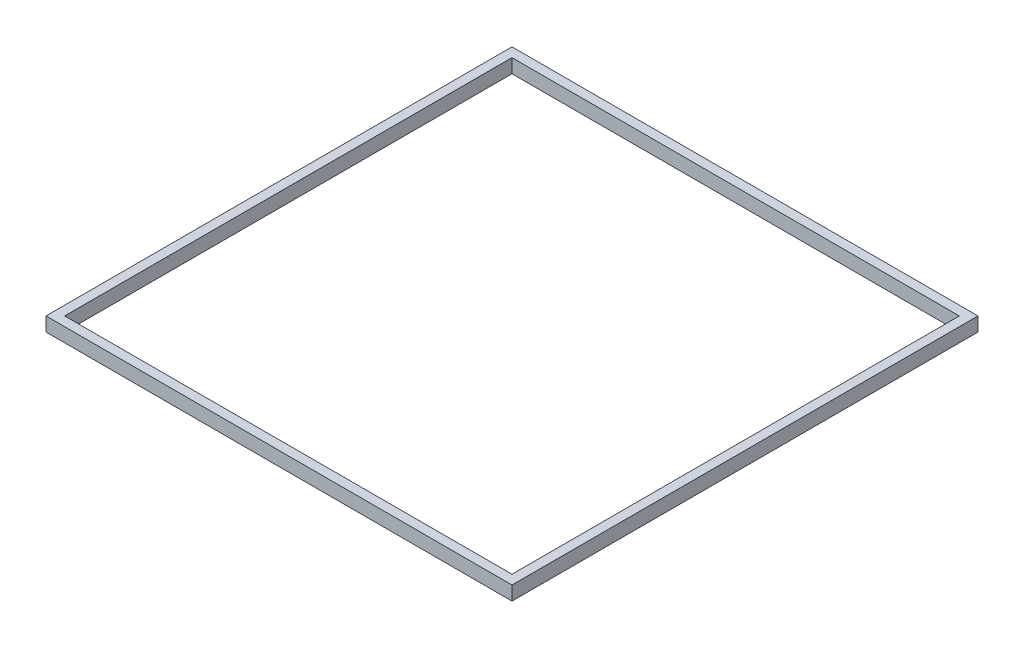
SolidWorks part; units mm, degrees
ref_plane "Front Plane" through (0, 0, 0) normal (0, 0, 1) x (1, 0, 0)
ref_plane "Top Plane" through (0, 0, 0) normal (0, 1, 0) x (1, 0, 0)
ref_plane "Right Plane" through (0, 0, 0) normal (1, 0, 0) x (0, 0, -1)
sketch "Sketch1" plane through (0, 0, 0) normal (0, 1, 0) x (1, 0, 0)
  line L0 (125, -125) -> (125, 125)
  line L1 (120, -120) -> (-120, -120)
  line L2 (120, -120) -> (120, 120)
  line L3 (120, 120) -> (-120, 120)
  line L4 (-120, -120) -> (-120, 120)
  line L5 (120, -120) -> (-120, 120) construction
  line L6 (120, 120) -> (-120, -120) construction
  line L7 (125, 125) -> (-125, 125)
  line L8 (-125, -125) -> (-125, 125)
  line L9 (125, -125) -> (-125, -125)
  point P0 (0, 0)
  dimension "D1" = 240
  dimension "D2" = 240
  dimension "D3" = 5
extrude "Boss-Extrude1" add sketch "Sketch1" along normal blind 7.5
